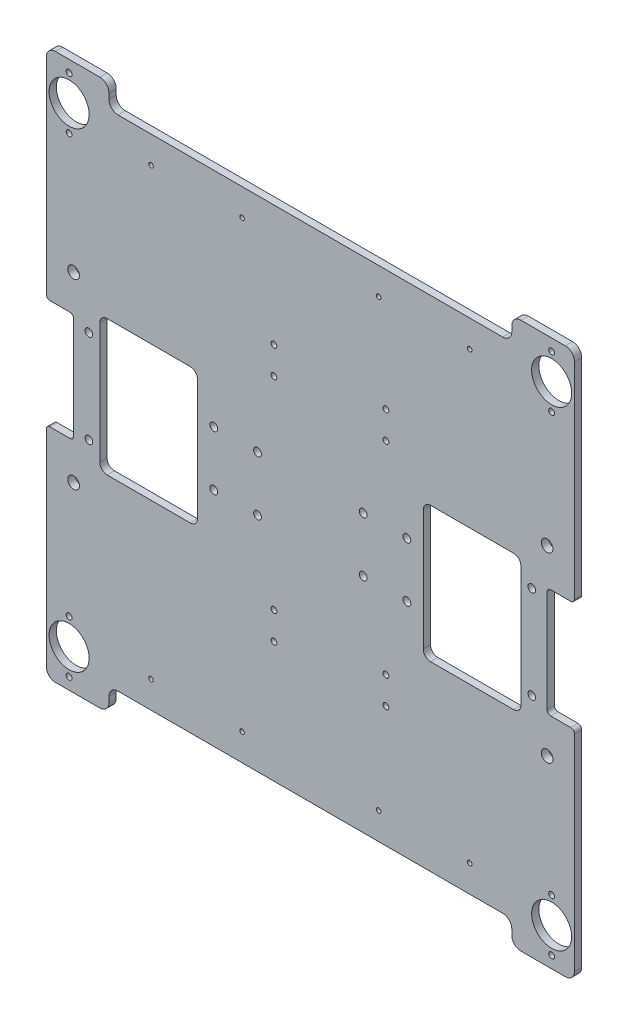
SolidWorks part; units mm, degrees
material "Alumina"
ref_plane "Front Plane" through (0, 0, 0) normal (0, 0, 1) x (1, 0, 0)
ref_plane "Top Plane" through (0, 0, 0) normal (0, 1, 0) x (1, 0, 0)
ref_plane "Right Plane" through (0, 0, 0) normal (1, 0, 0) x (0, 0, -1)
ref_plane "Plane1" through (0, 150, 0) normal (0, 1, 0) x (1, 0, 0)
ref_plane "Plane2" through (0, -150, 0) normal (0, 1, 0) x (1, 0, 0)
ref_plane "Plane3" through (150, 0, 0) normal (1, 0, 0) x (0, 0, -1)
ref_plane "Plane4" through (-150, 0, 0) normal (1, 0, 0) x (0, 0, -1)
sketch "Sketch2" plane through (0, 0, 0) normal (0, 0, 1) x (1, 0, 0)
  line L0 (0, -10.2) -> (0, 50.0764) construction
  line L5 (-53, 40) -> (-53, 10) construction
  line L23 (-140, 175) -> (-115.6003, 175)
  line L24 (139.6652, 116) -> (168.3348, 116) construction
  line L40 (-152.1866, -81.0661) -> (-123.5266, -81.0661) construction
  line L47 (-66, 62.1714) -> (-111.5977, 62.1714)
  line L48 (66, 62.1714) -> (111.5977, 62.1714)
  line L49 (62, 58.1714) -> (62, -8.1714)
  line L50 (66, -12.1714) -> (111.5977, -12.1714)
  line L51 (115.5977, 58.1714) -> (115.5977, -8.1714)
  line L52 (62, 62.1714) -> (115.5977, -12.1714) construction
  line L53 (62, -12.1714) -> (115.5977, 62.1714) construction
  line L54 (-62, 58.1714) -> (-62, -8.1714)
  line L55 (-66, -12.1714) -> (-111.5977, -12.1714)
  line L56 (-115.5977, 58.1714) -> (-115.5977, -8.1714)
  line L57 (177.1787, -66.0847) -> (177.1787, 11.9153) construction
  line L66 (94.5, 117.9861) -> (-94.5, 117.9861) construction
  line L70 (-121.5977, 50.5) -> (-121.5977, -0.5) construction
  line L73 (-145, 170) -> (-145, 57)
  line L74 (162.5, 25) -> (139.6652, 25) construction
  line L79 (-145, -7) -> (-145, -120)
  line L80 (-143, -5) -> (-132, -5)
  line L82 (-143, 55) -> (-132, 55)
  line L83 (-130, -3) -> (-130, 53)
  line L84 (-145.4163, 25) -> (-130, 55) construction
  line L85 (-145.4163, 25) -> (-130, -5) construction
  line L88 (145.4163, 25) -> (130, -5) construction
  line L89 (145.4163, 25) -> (130, 55) construction
  line L90 (121.5977, 50.5) -> (121.5977, -0.5) construction
  line L91 (130, -3) -> (130, 53)
  line L92 (143, 55) -> (132, 55)
  line L93 (143, -5) -> (132, -5)
  line L94 (145, -7) -> (145, -120)
  line L95 (145, 170) -> (145, 57)
  line L97 (140, -125) -> (115.6003, -125)
  line L99 (-105.6003, 162) -> (105.6003, 162)
  line L100 (115.6003, 175) -> (140, 175)
  line L101 (-105.6003, -112) -> (105.6003, -112)
  line L102 (-115.6003, -125) -> (-140, -125)
  line L103 (97.0952, -112) -> (105.6003, -112) construction
  line L104 (-97.0952, -112) -> (-105.6003, -112) construction
  line L106 (110.6003, -120) -> (110.6003, -117)
  line L108 (-110.6003, -120) -> (-110.6003, -117)
  line L109 (110.6003, 170) -> (110.6003, 167)
  line L110 (-97.0952, 162) -> (-105.6003, 162) construction
  line L111 (-110.6003, 170) -> (-110.6003, 167)
  circle A1 centre (-132.4733, 168.5604) radius 1.5
  circle A2 centre (-132.4733, 139.8908) radius 1.5
  circle A3 centre (132.4733, 168.5604) radius 1.5
  circle A4 centre (132.4733, 139.8908) radius 1.5
  circle A9 centre (132.4733, 154.2256) radius 11
  circle A10 centre (-132.4733, 154.2256) radius 11
  circle A17 centre (121.5977, -0.5) radius 1.65
  circle A18 centre (121.5977, 50.5) radius 1.65
  circle A19 centre (-121.5977, -0.5) radius 1.65
  circle A20 centre (-121.5977, 50.5) radius 1.65
  circle A27 centre (-29, 10) radius 1.5
  circle A32 centre (-29, 40) radius 1.5
  circle A33 centre (-53, 40) radius 1.5
  circle A34 centre (-53, 10) radius 1.5
  circle A35 centre (53, 10) radius 1.5
  circle A36 centre (29, 10) radius 1.5
  circle A37 centre (29, 40) radius 1.5
  circle A38 centre (53, 40) radius 1.5
  arc A48 (62, -8.1714) -> (66, -12.1714) centre (66, -8.1714) ccw
  arc A49 (111.5977, -12.1714) -> (115.5977, -8.1714) centre (111.5977, -8.1714) ccw
  arc A50 (111.5977, 62.1714) -> (115.5977, 58.1714) centre (111.5977, 58.1714) cw
  arc A51 (66, 62.1714) -> (62, 58.1714) centre (66, 58.1714) ccw
  arc A52 (-111.5977, 62.1714) -> (-115.5977, 58.1714) centre (-111.5977, 58.1714) ccw
  arc A53 (-66, 62.1714) -> (-62, 58.1714) centre (-66, 58.1714) cw
  arc A54 (-62, -8.1714) -> (-66, -12.1714) centre (-66, -8.1714) cw
  arc A55 (-111.5977, -12.1714) -> (-115.5977, -8.1714) centre (-111.5977, -8.1714) cw
  circle A68 centre (132.4733, -118.5604) radius 1.5
  circle A69 centre (132.4733, -89.8908) radius 1.5
  circle A70 centre (132.4733, -104.2256) radius 11
  circle A71 centre (-132.4733, -104.2256) radius 11
  circle A72 centre (-132.4733, -89.8908) radius 1.5
  circle A73 centre (-132.4733, -118.5604) radius 1.5
  arc A84 (-140, 175) -> (-145, 170) centre (-140, 170) ccw
  arc A85 (140, 175) -> (145, 170) centre (140, 170) cw
  arc A86 (140, -125) -> (145, -120) centre (140, -120) ccw
  arc A87 (-140, -125) -> (-145, -120) centre (-140, -120) cw
  circle A89 centre (130, 75) radius 1.5
  circle A93 centre (41.5, 95.575) radius 1
  circle A94 centre (41.5, 80.575) radius 1
  circle A95 centre (-20, 80.575) radius 1
  circle A96 centre (-20, 95.575) radius 1
  circle A98 centre (-20, -45.575) radius 1
  circle A99 centre (-20, -30.575) radius 1
  circle A100 centre (41.5, -30.575) radius 1
  circle A101 centre (41.5, -45.575) radius 1
  circle A102 centre (130, -25) radius 1.5
  circle A103 centre (-130, 75) radius 1.5
  circle A104 centre (-130, -25) radius 1.5
  arc A105 (-143, -5) -> (-145, -7) centre (-143, -7) ccw
  arc A106 (-132, -5) -> (-130, -3) centre (-132, -3) ccw
  arc A107 (-143, 55) -> (-145, 57) centre (-143, 57) cw
  arc A108 (-132, 55) -> (-130, 53) centre (-132, 53) cw
  arc A109 (143, -5) -> (145, -7) centre (143, -7) cw
  arc A110 (132, -5) -> (130, -3) centre (132, -3) cw
  arc A111 (143, 55) -> (145, 57) centre (143, 57) ccw
  arc A112 (132, 55) -> (130, 53) centre (132, 53) ccw
  arc A113 (115.6003, -125) -> (110.6003, -120) centre (115.6003, -120) cw
  arc A114 (110.6003, -117) -> (105.6003, -112) centre (105.6003, -117) ccw
  arc A115 (-110.6003, -117) -> (-105.6003, -112) centre (-105.6003, -117) cw
  arc A116 (-115.6003, -125) -> (-110.6003, -120) centre (-115.6003, -120) ccw
  circle A117 centre (87.5, 147.175) radius 1
  circle A118 centre (37.5, 147.175) radius 1
  circle A119 centre (-37.5, 147.175) radius 1
  circle A120 centre (-87.5, 147.175) radius 1
  circle A121 centre (-87.5, -97.175) radius 1
  circle A122 centre (-37.5, -97.175) radius 1
  circle A123 centre (37.5, -97.175) radius 1
  circle A124 centre (87.5, -97.175) radius 1
  arc A125 (110.6003, 167) -> (105.6003, 162) centre (105.6003, 167) cw
  arc A126 (115.6003, 175) -> (110.6003, 170) centre (115.6003, 170) ccw
  arc A127 (-115.6003, 175) -> (-110.6003, 170) centre (-115.6003, 170) cw
  arc A128 (-110.6003, 167) -> (-105.6003, 162) centre (-105.6003, 167) ccw
  point P0 (0, 0)
  point P2 (0, 0)
  point P4 (0, 150)
  point P7 (-145.4163, 25)
  point P11 (-121.5977, 25)
  point P12 (88.7989, 25)
  point P15 (-145, 175)
  point P23 (-53, 25)
  point P24 (0, -20)
  point P32 (145, 175)
  point P33 (-130, 25)
  point P46 (145, -125)
  point P82 (177.1787, -27.0847)
  point P108 (-145, -125)
  point P111 (-115.5977, 25)
  point P112 (145.4163, 25)
  point P122 (0, 75)
  point P132 (-62, 25)
  point P145 (0, 162)
  point P148 (112.1721, -112)
  point P152 (0, 0)
  point P167 (-145, -5)
  point P173 (-145, 55)
  point P183 (0, -25)
  point P189 (145, -5)
  point P195 (145, 55)
  point P212 (110.6003, -112)
  point P213 (0, 0)
  point P224 (0, -100)
  point P225 (-110.6003, -112)
  point P232 (110.6003, 162)
  point P239 (-110.6003, 162)
  dimension "D3" = 51
  dimension "D7" = 145
  dimension "D8" = 3
  dimension "D9" = 5
  dimension "D10" = 22
  dimension "D11" = 74.3428
  dimension "D12" = 13
  dimension "D13" = 53.5977
  dimension "D16" = 62
  dimension "D17" = 15
  dimension "D18" = 60
  dimension "D19" = 3.3
  dimension "D6" = 14.3348
  dimension "D20" = 14.3348
  dimension "D21" = 150
  dimension "D23" = 3
  dimension "D24" = 3
  dimension "D25" = 3
  dimension "D26" = 3
  dimension "D27" = 3
  dimension "D29" = 24
  dimension "D31" = 4
  dimension "D32" = 3
  dimension "D33" = 3
  dimension "D34" = 2
  dimension "D35" = 37.1714
  dimension "D36" = 3
  dimension "D37" = 2
  dimension "D38" = 2
  dimension "D39" = 2
  dimension "D40" = 2
  dimension "D41" = 37.5
  dimension "D42" = 14.825
  dimension "D44" = 50
  dimension "D45" = 37.5
  dimension "D46" = 50
  dimension "D47" = 5
  dimension "D4" = 3.3
  dimension "D5" = 6
  dimension "D22" = 15
  dimension "D28" = 24
  dimension "D30" = 29
  dimension "D15" = 3
  dimension "D14" = 34.3997
extrude "Boss-Extrude1" add sketch "Sketch2" along normal blind 4
hole_wizard "M4 Clearance Hole1" positions "3DSketch1" profile "Sketch3" hole size "M4" standard "ISO"
sketch3d "3DSketch1"
  line L0 (-53, 40, 4) -> (-53, 40, 0) construction
  line L1 (-29, 40, 4) -> (-29, 40, 0) construction
  line L2 (-29, 10, 4) -> (-29, 10, 0) construction
  line L3 (-53, 10, 4) -> (-53, 10, 0) construction
  line L4 (29, 40, 4) -> (29, 40, 0) construction
  line L5 (53, 40, 4) -> (53, 40, 0) construction
  line L6 (53, 10, 4) -> (53, 10, 0) construction
  line L7 (29, 10, 4) -> (29, 10, 0) construction
  point P0 (-53, 40, 4)
  point P4 (-29, 40, 4)
  point P8 (-29, 10, 4)
  point P12 (-53, 10, 4)
  point P16 (29, 40, 4)
  point P20 (53, 40, 4)
  point P24 (53, 10, 4)
  point P28 (29, 10, 4)
sketch "Sketch3" plane through (-53, 40, 4) normal (1, 0, 0) x (0, -1, 0)
  line L0 (0, 0) -> (0, 7.2919)
  line L1 (0, 7.2919) -> (2.15, 6)
  line L2 (2.15, 6) -> (2.15, 0)
  line L5 (2.15, 0) -> (0, 0)
  line L10 (0, 7.2919) -> (-2.15, 6) construction
  line L11 (0, -6.35) -> (0, 107.95) construction
  dimension "Hole Dia." = 4.3
  dimension "Hole Depth" = 6
  dimension "Drill Angle" = 118
hole_wizard "M3 Clearance Hole2" positions "3DSketch3" profile "Sketch5" hole size "M3" standard "ISO"
sketch3d "3DSketch3"
  line L0 (-132.4733, 168.5604, 4) -> (-132.4733, 168.5604, 0) construction
  line L1 (-132.4733, 139.8908, 4) -> (-132.4733, 139.8908, 0) construction
  line L2 (132.4733, 139.8908, 4) -> (132.4733, 139.8908, 0) construction
  line L3 (132.4733, 168.5604, 4) -> (132.4733, 168.5604, 0) construction
  line L4 (41.5, 80.575, 4) -> (41.5, 80.575, 0) construction
  line L5 (41.5, 95.575, 4) -> (41.5, 95.575, 0) construction
  line L6 (-20, 95.575, 4) -> (-20, 95.575, 0) construction
  line L7 (-20, 80.575, 4) -> (-20, 80.575, 0) construction
  line L8 (41.5, -30.575, 4) -> (41.5, -30.575, 0) construction
  line L9 (41.5, -45.575, 4) -> (41.5, -45.575, 0) construction
  line L10 (-20, -45.575, 4) -> (-20, -45.575, 0) construction
  line L11 (-20, -30.575, 4) -> (-20, -30.575, 0) construction
  line L12 (132.4733, -89.8908, 4) -> (132.4733, -89.8908, 0) construction
  line L13 (132.4733, -118.5604, 4) -> (132.4733, -118.5604, 0) construction
  line L14 (-132.4733, -118.5604, 4) -> (-132.4733, -118.5604, 0) construction
  line L15 (-132.4733, -89.8908, 4) -> (-132.4733, -89.8908, 0) construction
  point P0 (-132.4733, 168.5604, 4)
  point P4 (-132.4733, 139.8908, 4)
  point P8 (132.4733, 139.8908, 4)
  point P12 (132.4733, 168.5604, 4)
  point P16 (41.5, 80.575, 4)
  point P20 (41.5, 95.575, 4)
  point P24 (-20, 95.575, 4)
  point P28 (-20, 80.575, 4)
  point P32 (41.5, -30.575, 4)
  point P36 (41.5, -45.575, 4)
  point P40 (-20, -45.575, 4)
  point P44 (-20, -30.575, 4)
  point P48 (132.4733, -89.8908, 4)
  point P52 (132.4733, -118.5604, 4)
  point P56 (-132.4733, -118.5604, 4)
  point P60 (-132.4733, -89.8908, 4)
sketch "Sketch5" plane through (-132.4733, 168.5604, 4) normal (1, 0, 0) x (0, -1, 0)
  line L0 (0, 0) -> (0, 6.9614)
  line L1 (0, 6.9614) -> (1.6, 6)
  line L2 (1.6, 6) -> (1.6, 0)
  line L5 (1.6, 0) -> (0, 0)
  line L10 (0, 6.9614) -> (-1.6, 6) construction
  line L11 (0, -6.35) -> (0, 107.95) construction
  dimension "Hole Dia." = 3.2
  dimension "Hole Depth" = 6
  dimension "Drill Angle" = 118
hole_wizard "M5 Tapped Hole1" positions "3DSketch4" profile "Sketch6" tap size "M5" standard "ISO"
sketch3d "3DSketch4"
  line L0 (-121.5977, 50.5, 4) -> (-121.5977, 50.5, 0) construction
  line L1 (-121.5977, -0.5, 4) -> (-121.5977, -0.5, 0) construction
  line L2 (121.5977, -0.5, 4) -> (121.5977, -0.5, 0) construction
  line L3 (121.5977, 50.5, 4) -> (121.5977, 50.5, 0) construction
  point P0 (-121.5977, 50.5, 4)
  point P4 (-121.5977, -0.5, 4)
  point P8 (121.5977, -0.5, 4)
  point P12 (121.5977, 50.5, 4)
sketch "Sketch6" plane through (-121.5977, 50.5, 4) normal (1, 0, 0) x (0, -1, 0)
  line L0 (0, 0) -> (0, 13.6618)
  line L1 (0, 13.6618) -> (2.1, 12.4)
  line L2 (2.1, 12.4) -> (2.1, 0)
  line L5 (2.1, 0) -> (0, 0)
  line L10 (0, 13.6618) -> (-2.1, 12.4) construction
  line L11 (0, -6.35) -> (0, 107.95) construction
  dimension "Tap Drill Dia." = 4.2
  dimension "Tap Drill Depth" = 12.4
  dimension "Drill Angle" = 118
cosmetic thread "Hole Thread1" parameters "D1"=10, "D2"=5
cosmetic thread "Hole Thread2" parameters "D1"=10, "D2"=5
cosmetic thread "Hole Thread3" parameters "D1"=10, "D2"=5
cosmetic thread "Hole Thread4" parameters "D1"=10, "D2"=5
hole_wizard "M6 Clearance Hole1" positions "3DSketch5" profile "Sketch7" hole size "M6" standard "ISO"
sketch3d "3DSketch5"
  line L0 (-130, 75, 4) -> (-130, 75, 0) construction
  line L1 (130, 75, 4) -> (130, 75, 0) construction
  line L2 (130, -25, 4) -> (130, -25, 0) construction
  line L3 (-130, -25, 4) -> (-130, -25, 0) construction
  point P0 (-130, 75, 4)
  point P4 (130, 75, 4)
  point P8 (130, -25, 4)
  point P12 (-130, -25, 4)
sketch "Sketch7" plane through (-130, 75, 4) normal (1, 0, 0) x (0, -1, 0)
  line L0 (0, 0) -> (0, 16.9228)
  line L1 (0, 16.9228) -> (3.2, 15)
  line L2 (3.2, 15) -> (3.2, 0)
  line L5 (3.2, 0) -> (0, 0)
  line L10 (0, 16.9228) -> (-3.2, 15) construction
  line L11 (0, -6.35) -> (0, 107.95) construction
  dimension "Hole Dia." = 6.4
  dimension "Hole Depth" = 15
  dimension "Drill Angle" = 118
hole_wizard "M3 Tapped Hole2" positions "3DSketch8" profile "Sketch9" tap size "M3" standard "ISO"
sketch3d "3DSketch8"
  line L0 (-87.5, 147.175, 4) -> (-87.5, 147.175, 0) construction
  line L1 (-37.5, 147.175, 4) -> (-37.5, 147.175, 0) construction
  line L2 (37.5, 147.175, 4) -> (37.5, 147.175, 0) construction
  line L3 (87.5, 147.175, 4) -> (87.5, 147.175, 0) construction
  line L4 (87.5, -97.175, 4) -> (87.5, -97.175, 0) construction
  line L5 (37.5, -97.175, 4) -> (37.5, -97.175, 0) construction
  line L6 (-37.5, -97.175, 4) -> (-37.5, -97.175, 0) construction
  line L7 (-87.5, -97.175, 4) -> (-87.5, -97.175, 0) construction
  point P0 (-87.5, 147.175, 4)
  point P4 (-37.5, 147.175, 4)
  point P15 (37.5, 147.175, 4)
  point P19 (87.5, 147.175, 4)
  point P23 (87.5, -97.175, 4)
  point P27 (37.5, -97.175, 4)
  point P31 (-37.5, -97.175, 4)
  point P35 (-87.5, -97.175, 4)
sketch "Sketch9" plane through (-87.5, 147.175, 4) normal (1, 0, 0) x (0, -1, 0)
  line L0 (0, 0) -> (0, 8.2511)
  line L1 (0, 8.2511) -> (1.25, 7.5)
  line L2 (1.25, 7.5) -> (1.25, 0)
  line L5 (1.25, 0) -> (0, 0)
  line L10 (0, 8.2511) -> (-1.25, 7.5) construction
  line L11 (0, -6.35) -> (0, 107.95) construction
  dimension "Tap Drill Dia." = 2.5
  dimension "Tap Drill Depth" = 7.5
  dimension "Drill Angle" = 118
cosmetic thread "Hole Thread5" parameters "D1"=6, "D2"=3
cosmetic thread "Hole Thread6" parameters "D1"=6, "D2"=3
cosmetic thread "Hole Thread7" parameters "D1"=6, "D2"=3
cosmetic thread "Hole Thread8" parameters "D1"=6, "D2"=3
cosmetic thread "Hole Thread9" parameters "D1"=6, "D2"=3
cosmetic thread "Hole Thread10" parameters "D1"=6, "D2"=3
cosmetic thread "Hole Thread11" parameters "D1"=6, "D2"=3
cosmetic thread "Hole Thread12" parameters "D1"=6, "D2"=3
